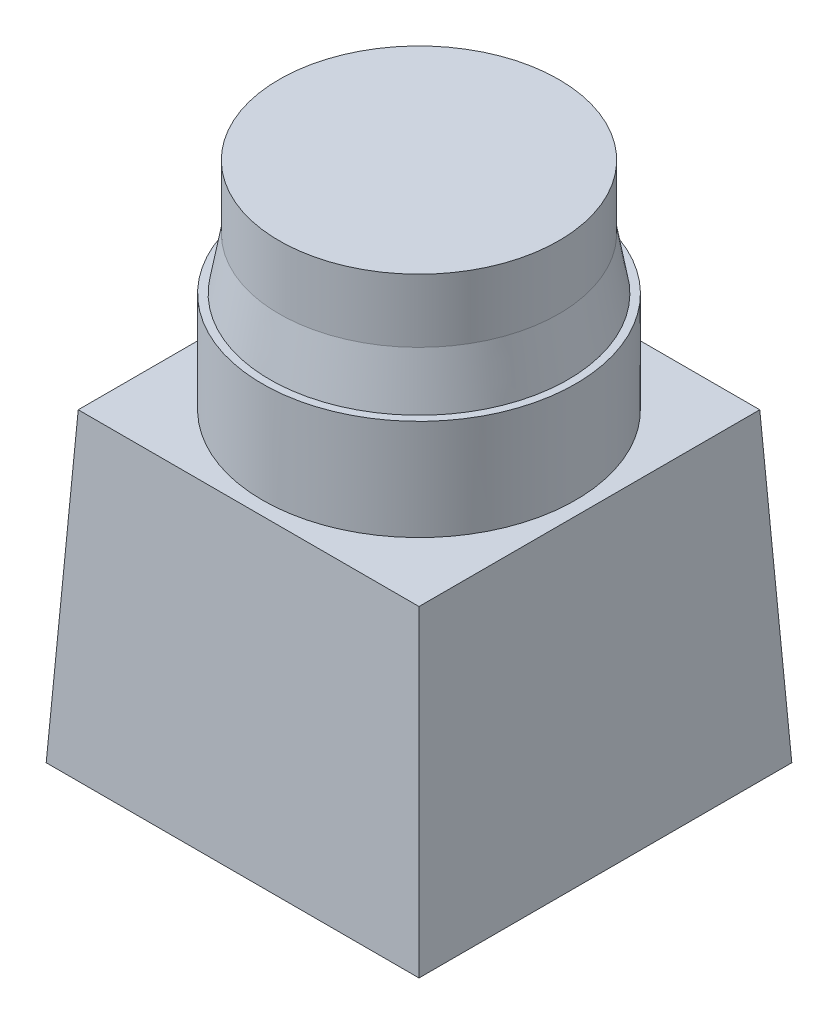
SolidWorks part; units mm, degrees
ref_plane "Plano frontal" through (0, 0, 0) normal (0, 0, 1) x (1, 0, 0)
ref_plane "Plano superior" through (0, 0, 0) normal (0, 1, 0) x (1, 0, 0)
ref_plane "Plano direito" through (0, 0, 0) normal (1, 0, 0) x (0, 0, -1)
sketch "Esboço1" plane through (0, 0, 0) normal (0, 1, 0) x (1, 0, 0)
  line L1 (-25, 25) -> (25, 25)
  line L2 (-25, 25) -> (-25, -25)
  line L3 (-25, -25) -> (25, -25)
  line L4 (25, 25) -> (25, -25)
  line L5 (-25, 25) -> (25, -25) construction
  line L6 (-25, -25) -> (25, 25) construction
  point P0 (0, 0)
  dimension "D1" = 50
  dimension "D2" = 50
extrude "Ressalto-extrusão1" add sketch "Esboço1" along normal blind 41 draft 3
sketch "Esboço2" plane through (0, 0, 0) normal (1, 0, 0) x (0, 0, -1)
  line L0 (0, 41) -> (0, 70) construction
  line L1 (-22.8513, 41) -> (22.8513, 41) construction
  line L2 (0, 70) -> (18.75, 70)
  line L3 (18.75, 70) -> (18.75, 61.5)
  line L4 (18.75, 61.5) -> (20, 54.5)
  line L5 (21, 41) -> (21, 54.5)
  line L6 (20, 54.5) -> (21, 54.5)
  line L7 (0, 41) -> (21, 41)
  line L8 (21, 41) -> (0, 41)
  dimension "D1" = 29
  dimension "D2" = 40
  dimension "D3" = 37.5
  dimension "D4" = 42
  dimension "D5" = 20.5
  dimension "D6" = 13.5
revolve "Revolução1" add sketch "Esboço2" angle 360 about L0
